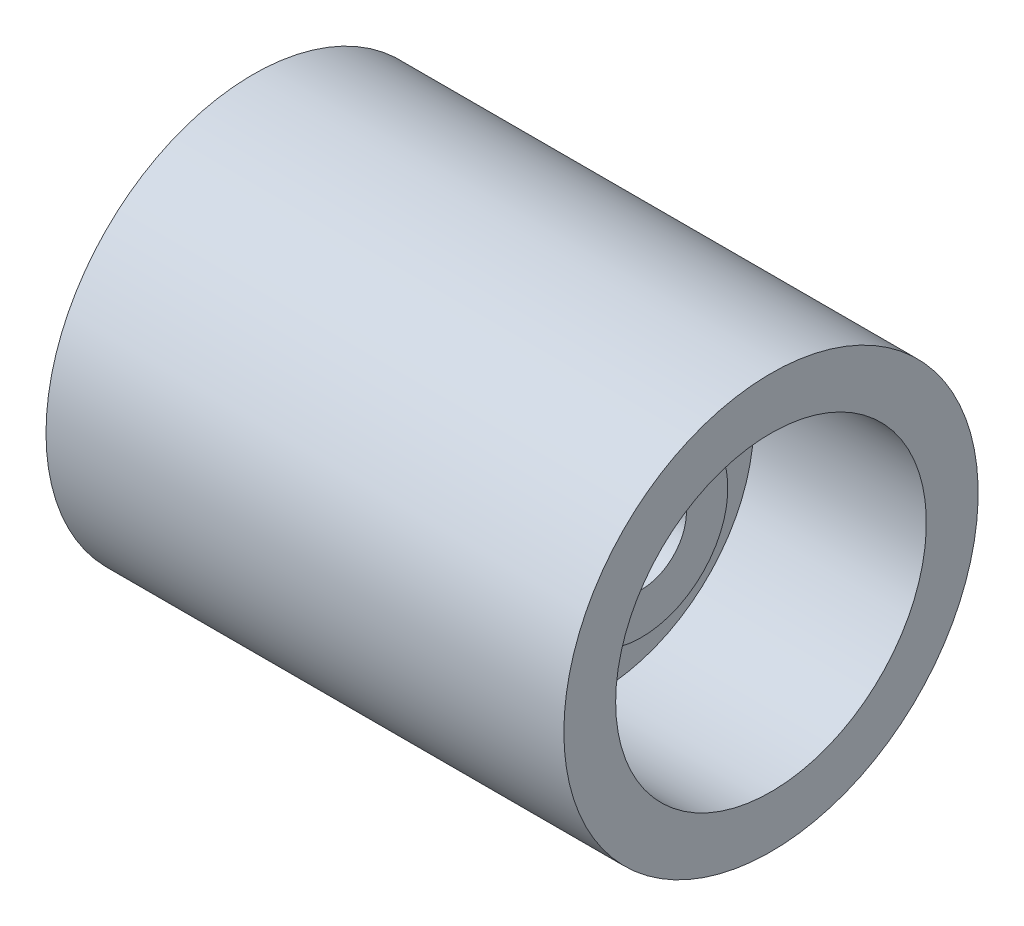
SolidWorks part; units mm, degrees
ref_plane "Alzado" through (0, 0, 0) normal (0, 0, 1) x (1, 0, 0)
ref_plane "Planta" through (0, 0, 0) normal (0, 1, 0) x (1, 0, 0)
ref_plane "Vista lateral" through (0, 0, 0) normal (1, 0, 0) x (0, 0, -1)
sketch "Sketch1" plane through (0, 0, 0) normal (0, 0, 1) x (1, 0, 0)
  line L0 (0, 0) -> (12758.8411, 0) construction
  line L1 (-7.5, 0) -> (-7.5, 5)
  line L2 (-7.5, 5) -> (-5, 5)
  line L3 (-5, 5) -> (-5, 9)
  line L4 (-5, 9) -> (-15, 9)
  line L5 (-15, 9) -> (-15, 12)
  line L6 (-15, 12) -> (15, 12)
  line L7 (15, 12) -> (15, 9)
  line L8 (15, 9) -> (5, 9)
  line L9 (5, 9) -> (5, 5)
  line L10 (5, 5) -> (7.5, 5)
  line L11 (7.5, 5) -> (7.5, 0)
  line L12 (-7.5, 0) -> (7.5, 0)
  point P20 (0, 12)
  dimension "D1" = 12
  dimension "D2" = 30
  dimension "D3" = 15
  dimension "D4" = 5
  dimension "D5" = 10
  dimension "D6" = 3
revolve "Revolve1" add sketch "Sketch1" angle 360 about L0
sketch "Sketch2" plane through (-7.5, 0, 0) normal (-1, 0, 0) x (0, 0, 1)
  circle A0 centre (0, 0) radius 2.6
  dimension "D1" = 5.2
extrude "Cut-Extrude1" cut sketch "Sketch2" against normal through all
